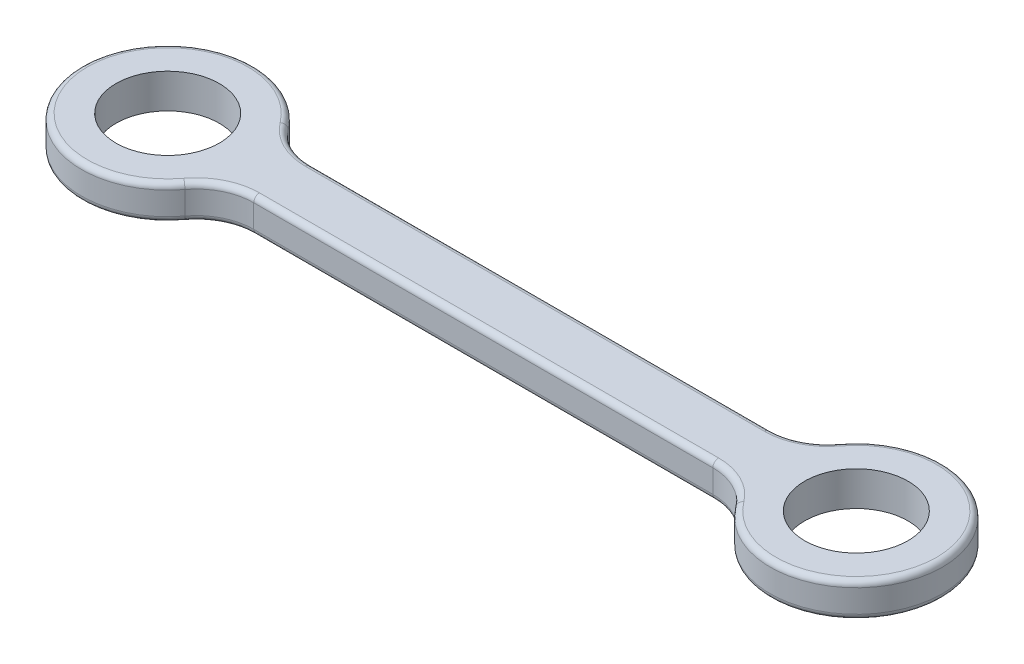
SolidWorks part; units mm, degrees
ref_plane "Front Plane" through (0, 0, 0) normal (0, 0, 1) x (1, 0, 0)
ref_plane "Top Plane" through (0, 0, 0) normal (0, 1, 0) x (1, 0, 0)
ref_plane "Right Plane" through (0, 0, 0) normal (1, 0, 0) x (0, 0, -1)
sketch "Sketch1" plane through (0, 0, 0) normal (0, 1, 0) x (1, 0, 0)
  line L1 (-28.046, 5) -> (51.954, 5)
  line L3 (-28.046, -5) -> (51.954, -5)
  circle A0 centre (-48.046, 0) radius 9
  circle A1 centre (71.954, 0) radius 9
  arc A2 (-36.046, 9) -> (-36.046, -9) centre (-48.046, 0) ccw
  arc A3 (59.954, -9) -> (59.954, 9) centre (71.954, 0) ccw
  arc A4 (59.954, 9) -> (51.954, 5) centre (51.954, 15) cw
  arc A5 (59.954, -9) -> (51.954, -5) centre (51.954, -15) ccw
  arc A6 (-28.046, -5) -> (-36.046, -9) centre (-28.046, -15) ccw
  arc A7 (-28.046, 5) -> (-36.046, 9) centre (-28.046, 15) cw
  point P6 (-48.046, 5)
  point P8 (31.954, 5)
  point P9 (-48.046, -5)
  point P10 (49.3563, -5)
  dimension "D1" = 18
  dimension "D2" = 18
  dimension "D3" = 30
  dimension "D4" = 30
  dimension "D5" = 10
  dimension "D6" = 120
  dimension "D7" = 10
extrude "Boss-Extrude1" add sketch "Sketch1" along normal blind 6
fillet "Fillet1" radius 1 16 edges at (-63.046, 0, 0) (-32.5181, 0, -6.0557) (11.954, 0, -5) (56.4262, 0, -6.0557) (86.954, 0, 0) (56.4262, 0, 6.0557) (11.954, 0, 5) (-32.5181, 6, 6.0557) (-63.046, 6, 0) (-32.5181, 6, -6.0557) (11.954, 6, -5) (56.4262, 6, -6.0557) (86.954, 6, 0) (56.4262, 6, 6.0557) (-32.5181, 0, 6.0557) (11.954, 6, 5)
